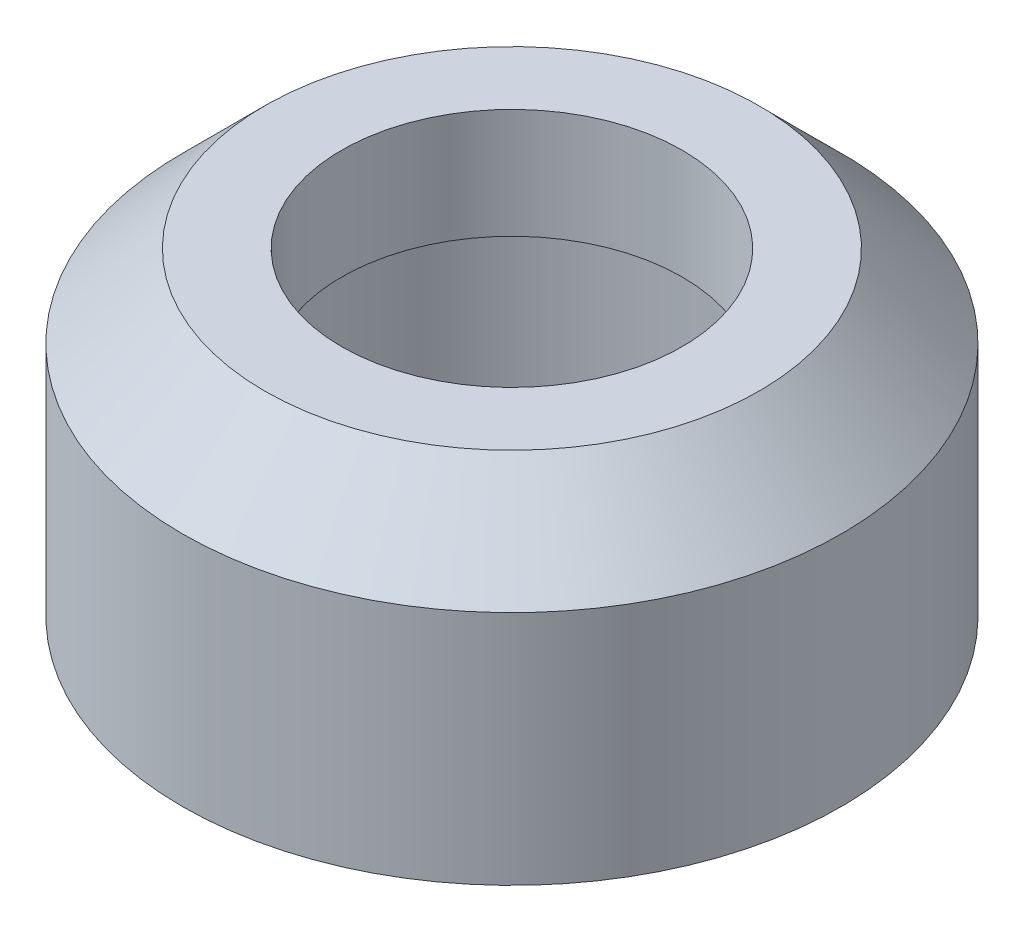
SolidWorks part; units mm, degrees
ref_plane "Front Plane" through (0, 0, 0) normal (0, 0, 1) x (1, 0, 0)
ref_plane "Top Plane" through (0, 0, 0) normal (0, 1, 0) x (1, 0, 0)
ref_plane "Right Plane" through (0, 0, 0) normal (1, 0, 0) x (0, 0, -1)
sketch "Sketch1" plane through (0, 0, 0) normal (0, 1, 0) x (1, 0, 0)
  circle A0 centre (0, 0) radius 3.1
  circle A1 centre (0, 0) radius 6
  dimension "D1" = 6.2
  dimension "D2" = 12
extrude "Boss-Extrude1" add sketch "Sketch1" along normal blind 5.8
sketch "Sketch2" plane through (0, 0, 0) normal (0, -1, 0) x (1, 0, 0)
  circle A0 centre (0, 0) radius 4.1
  dimension "D1" = 8.2
extrude "Cut-Extrude1" cut sketch "Sketch2" against normal blind 3.8
chamfer "Chamfer1" distance 1.5 angle 45 1 edges at (0, 5.8, 6)
